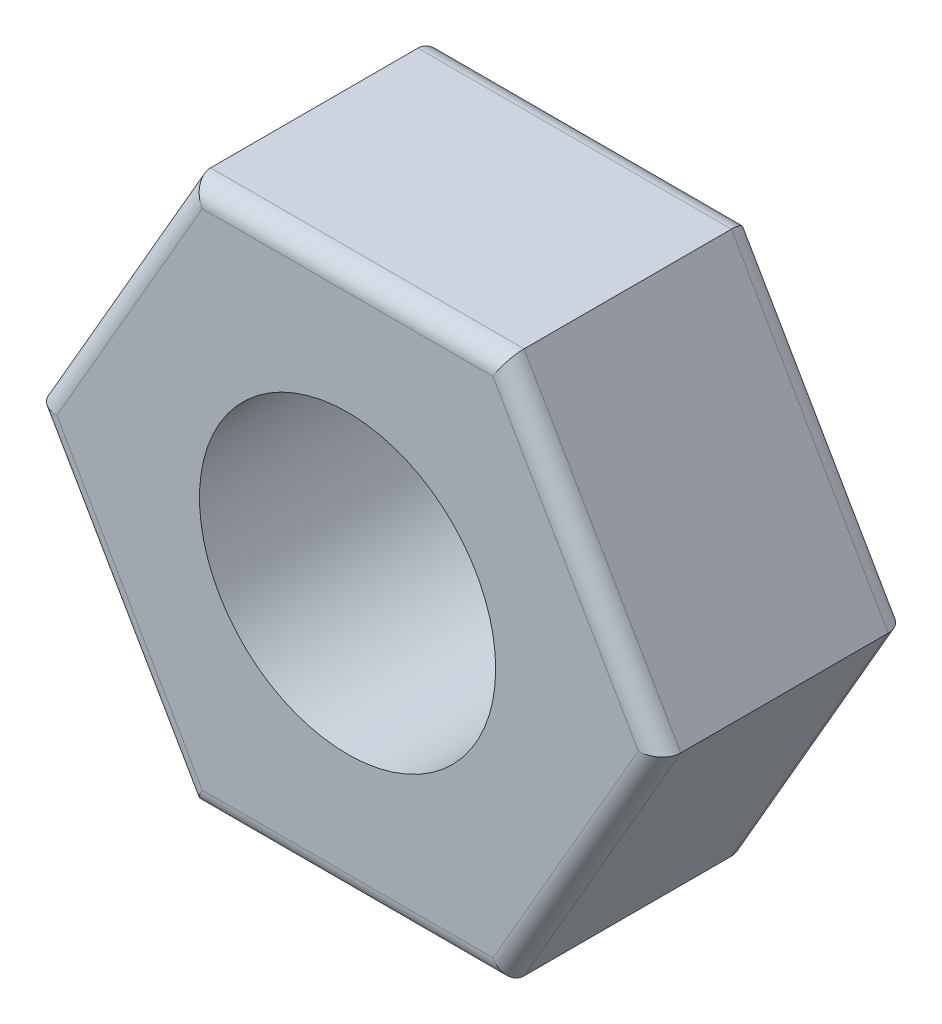
SolidWorks part; units mm, degrees
ref_plane "前视基准面" through (0, 0, 0) normal (0, 0, 1) x (1, 0, 0)
ref_plane "上视基准面" through (0, 0, 0) normal (0, 1, 0) x (1, 0, 0)
ref_plane "右视基准面" through (0, 0, 0) normal (1, 0, 0) x (0, 0, -1)
other "Configuration Table"
sketch "草图1" plane through (0, 0, 0) normal (0, 0, 1) x (1, 0, 0)
  line L1 (1.5877, -2.75) -> (3.1754, 0)
  line L2 (3.1754, 0) -> (1.5877, 2.75)
  line L3 (1.5877, 2.75) -> (-1.5877, 2.75)
  line L4 (-1.5877, 2.75) -> (-3.1754, 0)
  line L5 (-3.1754, 0) -> (-1.5877, -2.75)
  line L6 (-1.5877, -2.75) -> (1.5877, -2.75)
  circle A0 centre (0, 0) radius 2.75 construction
  circle A1 centre (0, 0) radius 1.5
  dimension "D2" = 3
  dimension "D1" = 5.5
extrude "凸台-拉伸1" add sketch "草图1" along normal blind 2.5
fillet "圆角1" radius 0.2 13 edges at (-2.3816, -1.375, 2.5) (-2.3816, 1.375, 2.5) (0, 2.75, 2.5) (2.3816, 1.375, 2.5) (2.3816, -1.375, 2.5) (0, -2.75, 2.5) (1.5, 0, 0) (2.3816, -1.375, 0) (2.3816, 1.375, 0) (0, 2.75, 0) (-2.3816, 1.375, 0) (-2.3816, -1.375, 0) (0, -2.75, 0)
